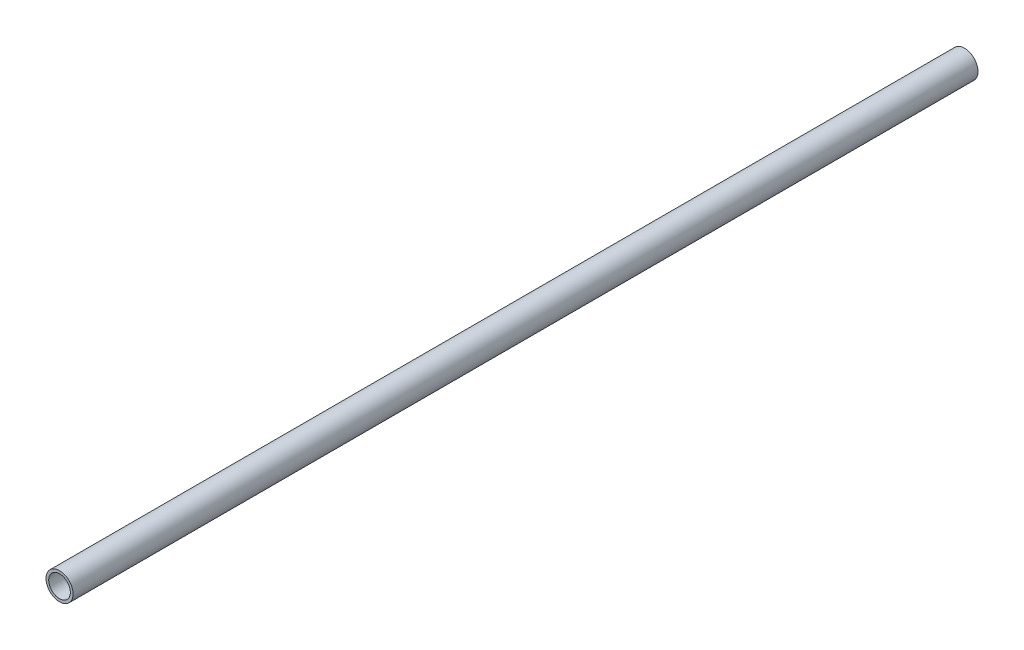
SolidWorks part; units mm, degrees
material "СТ3КП"
ref_plane "Спереди" through (0, 0, 0) normal (0, 0, 1) x (1, 0, 0)
ref_plane "Сверху" through (0, 0, 0) normal (0, 1, 0) x (1, 0, 0)
ref_plane "Справа" through (0, 0, 0) normal (1, 0, 0) x (0, 0, -1)
sketch "Эскиз1" plane through (0, 0, 0) normal (0, 0, 1) x (1, 0, 0)
  line L2 (1585.4946, 0) -> (-462.1132, 0) construction
  line L3 (0, 20) -> (0, 27) construction
  circle A0 centre (16, 16) radius 12.8
  circle A1 centre (16, 16) radius 16
  dimension "D2" = 32
  dimension "D1" = 3.2
extrude "Бобышка-Вытянуть1" add sketch "Эскиз1" along normal offset from surface 30 and the other way offset from surface (1040 mm away) 30
